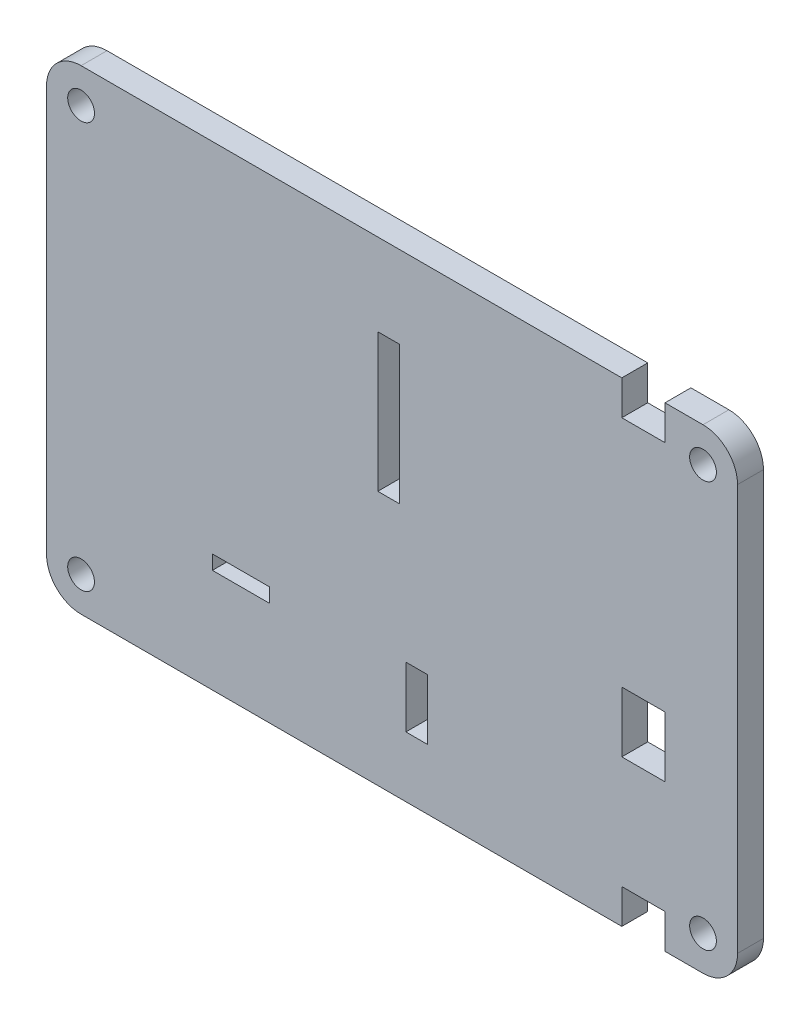
SolidWorks part; units mm, degrees
ref_plane "Plan de face" through (0, 0, 0) normal (0, 0, 1) x (1, 0, 0)
ref_plane "Plan de dessus" through (0, 0, 0) normal (0, 1, 0) x (1, 0, 0)
ref_plane "Plan de droite" through (0, 0, 0) normal (1, 0, 0) x (0, 0, -1)
sketch "Esquisse1" plane through (0, 0, 0) normal (0, 0, 1) x (1, 0, 0)
  line L0 (31.6, -3.5) -> (26.6, -3.5)
  line L1 (26.6, -3.5) -> (26.6, -10.5)
  line L2 (26.6, -10.5) -> (31.6, -10.5)
  line L3 (31.6, -10.5) -> (31.6, -3.5)
  line L4 (26.6, 27.5) -> (-36, 27.5)
  line L5 (26.6, 23.5) -> (26.6, 27.5)
  line L6 (31.6, 23.5) -> (26.6, 23.5)
  line L7 (31.6, 27.5) -> (31.6, 23.5)
  line L8 (36, 27.5) -> (31.6, 27.5)
  line L9 (40, -23.5) -> (40, 23.5)
  line L11 (31.6, -27.5) -> (36, -27.5)
  line L12 (31.6, -23.5) -> (31.6, -27.5)
  line L13 (26.6, -23.5) -> (31.6, -23.5)
  line L14 (26.6, -27.5) -> (26.6, -23.5)
  line L15 (-36, -27.5) -> (26.6, -27.5)
  line L17 (-40, 23.5) -> (-40, -23.5)
  line L18 (0.85, 18) -> (-1.65, 18)
  line L19 (-1.65, 18) -> (-1.65, 2)
  line L20 (-1.65, 2) -> (0.85, 2)
  line L21 (0.85, 2) -> (0.85, 18)
  line L22 (-20.8, -15.5) -> (-14.2, -15.5)
  line L23 (4.1, -20.5) -> (4.1, -13.5)
  line L24 (4.1, -13.5) -> (1.6, -13.5)
  line L25 (1.6, -13.5) -> (1.6, -20.5)
  line L26 (1.6, -20.5) -> (4.1, -20.5)
  line L27 (-20.8, -13.85) -> (-20.8, -15.5)
  line L28 (-14.2, -15.5) -> (-14.2, -13.85)
  line L29 (-14.2, -13.85) -> (-20.8, -13.85)
  arc A0 (-36, 27.5) -> (-40, 23.5) centre (-36, 23.5) ccw
  arc A1 (40, 23.5) -> (36, 27.5) centre (36, 23.5) ccw
  arc A2 (36, -27.5) -> (40, -23.5) centre (36, -23.5) ccw
  arc A3 (-40, -23.5) -> (-36, -27.5) centre (-36, -23.5) ccw
  circle A4 centre (-36, -23.5) radius 1.55
  circle A5 centre (-36, 23.5) radius 1.55
  circle A6 centre (36, 23.5) radius 1.55
  circle A7 centre (36, -23.5) radius 1.55
  dimension "D7" = 3.1
  dimension "D8" = 4
  dimension "D1" = 80
  dimension "D2" = 55
  dimension "D3" = 5
  dimension "D4" = 4
  dimension "D5" = 4
  dimension "D6" = 8.4
  dimension "D9" = 27
  dimension "D10" = 7
  dimension "D11" = 25.75
  dimension "D12" = 16
  dimension "D13" = 9.5
  dimension "D14" = 2.5
  dimension "D15" = 14
  dimension "D16" = 7
  dimension "D17" = 2.5
  dimension "D18" = 22.5
  dimension "D19" = 12
  dimension "D20" = 1.65
  dimension "D21" = 6.6
  dimension "D22" = 15.8
  dimension "D23" = 27.5
  dimension "D24" = 40
extrude "Boss.-Extru.1" add sketch "Esquisse1" along normal blind 3
